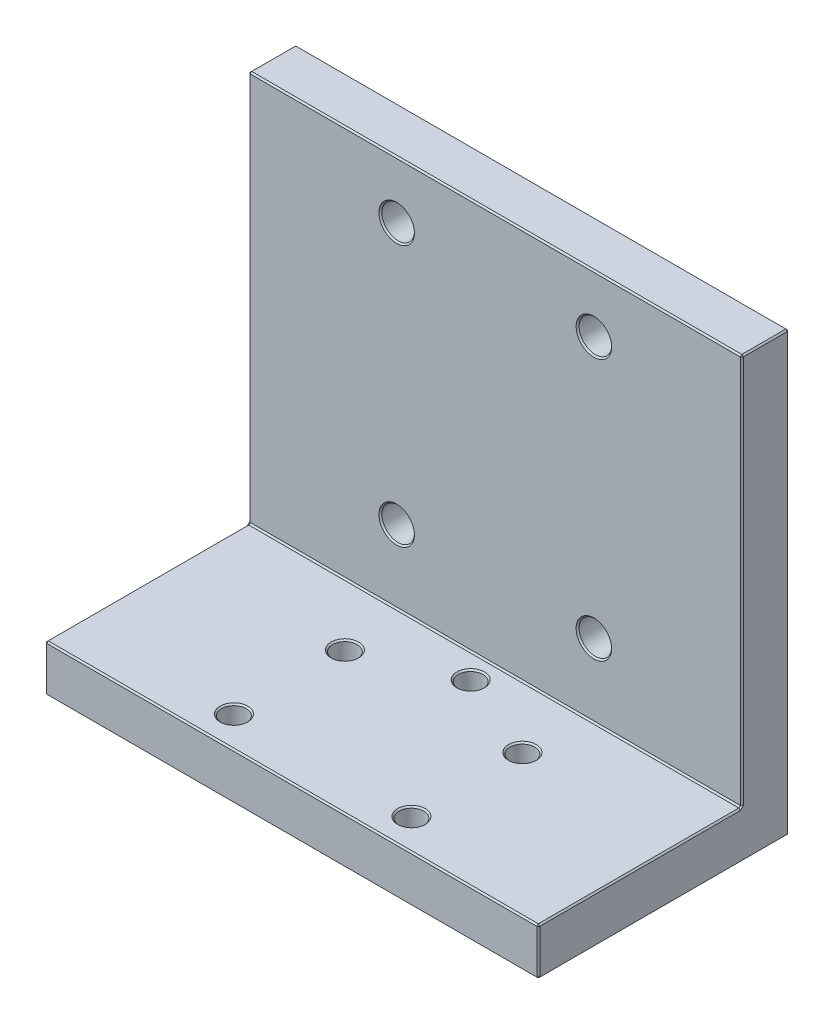
SolidWorks part; units mm, degrees
material "1060 Alloy"
ref_plane "Front Plane" through (0, 0, 0) normal (0, 0, 1) x (1, 0, 0)
ref_plane "Top Plane" through (0, 0, 0) normal (0, 1, 0) x (1, 0, 0)
ref_plane "Right Plane" through (0, 0, 0) normal (1, 0, 0) x (0, 0, -1)
sketch "Sketch1" plane through (0, 0, 0) normal (1, 0, 0) x (0, 0, -1)
  line L2 (0, 0) -> (0, 88.9)
  line L3 (0, 88.9) -> (-9.525, 88.9)
  line L4 (-9.525, 9.525) -> (-9.525, 88.9)
  line L5 (0, 0) -> (-50.8, 0)
  line L7 (-9.525, 9.525) -> (-50.8, 9.525)
  line L8 (-50.8, 0) -> (-50.8, 9.525)
  dimension "D1" = 9.525
  dimension "D2" = 88.9
  dimension "D3" = 50.8
extrude "Boss-Extrude1" add sketch "Sketch1" along normal mid plane 100
sketch "Sketch2" plane through (0, 0, 9.525) normal (0, 0, 1) x (1, 0, 0)
  line L0 (50, 0) -> (-50, 0) construction
  line L1 (20, 24.3) -> (-20, 24.3) construction
  line L2 (20, 24.3) -> (20, 77.3) construction
  line L3 (20, 77.3) -> (-20, 77.3) construction
  line L4 (-20, 24.3) -> (-20, 77.3) construction
  line L5 (20, 24.3) -> (-20, 77.3) construction
  line L6 (20, 77.3) -> (-20, 24.3) construction
  line L7 (50, 88.9) -> (50, 9.525) construction
  line L8 (0, 50.8) -> (0, 0) construction
  line L9 (-50, 101.6) -> (50, 101.6) construction
  line L10 (-50, 101.6) -> (-50, 0) construction
  line L11 (-50, 0) -> (50, 0) construction
  line L12 (50, 101.6) -> (50, 0) construction
  line L13 (-50, 88.9) -> (-50, 9.525) construction
  circle A0 centre (-20, 77.3) radius 3.3
  circle A1 centre (20, 77.3) radius 3.3
  circle A2 centre (20, 24.3) radius 3.3
  circle A3 centre (-20, 24.3) radius 3.3
  point P0 (0, 50.8)
  dimension "D1" = 6.6
  dimension "D2" = 40
  dimension "D3" = 53
  dimension "D5" = 101.6
  dimension "D4" = 50.8
extrude "Cut-Extrude1" cut sketch "Sketch2" against normal blind 100
sketch "Sketch3" plane through (0, 9.525, 0) normal (0, 1, 0) x (1, 0, 0)
  line L0 (0, 0) -> (0, -33.275) construction
  line L1 (18, -22.025) -> (-18, -22.025) construction
  line L2 (18, -22.025) -> (18, -44.525) construction
  line L3 (18, -44.525) -> (-18, -44.525) construction
  line L4 (-18, -22.025) -> (-18, -44.525) construction
  line L5 (18, -22.025) -> (-18, -44.525) construction
  line L6 (18, -44.525) -> (-18, -22.025) construction
  line L9 (50, 0) -> (-50, 0) construction
  circle A0 centre (-18, -22.025) radius 2.5
  circle A1 centre (-18, -44.525) radius 2.5
  circle A2 centre (18, -44.525) radius 2.5
  circle A3 centre (18, -22.025) radius 2.5
  circle A4 centre (0, -14.525) radius 2.5
  point P0 (0, -33.275)
  dimension "D1" = 5
  dimension "D2" = 22.5
  dimension "D3" = 36
  dimension "D4" = 7.5
  dimension "D5" = 14.525
extrude "Cut-Extrude2" cut sketch "Sketch3" against normal blind 100
chamfer "Chamfer1" distance 0.3 angle 45 36 edges at (-18, 9.525, 24.525) (-18, 9.525, 47.025) (18, 9.525, 47.025) (18, 9.525, 24.525) (0, 9.525, 17.025) (-16.7, 77.3, 9.525) (23.3, 77.3, 9.525) (23.3, 24.3, 9.525) (-16.7, 24.3, 9.525) (50, 9.525, 30.1625) (0, 9.525, 50.8) (-50, 9.525, 30.1625) (0, 88.9, 9.525) (50, 49.2125, 9.525) (0, 9.525, 9.525) (-50, 49.2125, 9.525) (0, 0, 0) (0, 88.9, 0) (50, 4.7625, 50.8) (50, 88.9, 4.7625) (50, 44.45, 0) (50, 0, 25.4) (0, 0, 50.8) (-50, 4.7625, 50.8) (-50, 88.9, 4.7625) (-50, 44.45, 0) (-50, 0, 25.4) (-16.7, 77.3, 0) (23.3, 77.3, 0) (23.3, 24.3, 0) (-16.7, 24.3, 0) (-18, 0, 24.525) (-18, 0, 47.025) (18, 0, 47.025) (18, 0, 24.525) (0, 0, 17.025)
equation "\"M5_tap\"=4.2mm\t\t\t\t\t\t\t' Below you can do mesurements as follows: cm, mm, ft, in, m, "
equation "\"M5_clearence\"=5.5mm"
equation "\"M6_tap\"=5mm"
equation "\"M6_clearence\"=6.6mm"
equation "\"D1@Sketch2\"=\"M6_clearence\""
equation "\"D1@Sketch3\"=\"M6_tap\""
equation "\"work_area_width\"=1100mm"
equation "\"work_area_depth\"=900mm"
equation "\"steel_base_width\"=3in\t"
equation "\"steel_base_height\"=2in"
equation "\"steel_base_wall_thickness\"=0.125in"
equation "\"steel_base_radius\"=6mm"
equation "\"steel_sides_width\"=3in\t\t\t\t\t'this tube is rotated so flip width/height"
equation "\"steel_sides_height\"=2in\t\t\t\t'this tube is rotated so flip width/height"
equation "\"steel_sides_wall_thickness\"=0.125in"
equation "\"steel_sides_radius\"=6mm"
equation "\"steel_gantry_width\"=4in\t\t\t\t'this tube is rotated so flip width/height"
equation "\"steel_gantry_height\"=3in\t\t\t\t'this tube is rotated so flip width/height"
equation "\"steel_gantry_wall_thickness\"=0.125in"
equation "\"steel_gantry_radius\"=6mm"
equation "\"steel_rollers_width\"=3in"
equation "\"steel_rollers_height\"=2in\t\t\t\t'keep as low as possible as this increases how big plastic parts are"
equation "\"steel_rollers_wall_thickness\"=0.125in"
equation "\"steel_rollers_radius\"=6mm"
equation "\"steel_zbox_width\"=4in\t\t\t\t\t'if the gantry height (rotated) is too thick, a wider zbox is necessary"
equation "\"steel_zbox_height\"=2in\t\t\t\t\t'hole patteren changes as the zbox and gantry height (rotated) changes."
equation "\"steel_zbox_wall_thickness\"=0.125in"
equation "\"steel_zbox_radius\"=6mm"
equation "\"alu_zangle_width\"=3.5in\t\t\t\t\t'check that it doesn't interfer with the gantry"
equation "\"alu_zangle_height\"=2in"
equation "\"alu_zangle_wall_thickness\"=0.375in\t\t\t'check that it doesn't interfer with the gantry"
equation "\"D1@Sketch1\"=\"alu_zangle_wall_thickness\""
equation "\"D2@Sketch1\"=\"alu_zangle_width\""
equation "\"D3@Sketch1\"=\"alu_zangle_height\""
equation "\"D5@Sketch2\"=\"steel_zbox_width\""
equation "\"D5@Sketch3\"=\"alu_zangle_wall_thickness\"+5"
equation "\"D4@Sketch2\"=\"steel_zbox_width\"/2"
